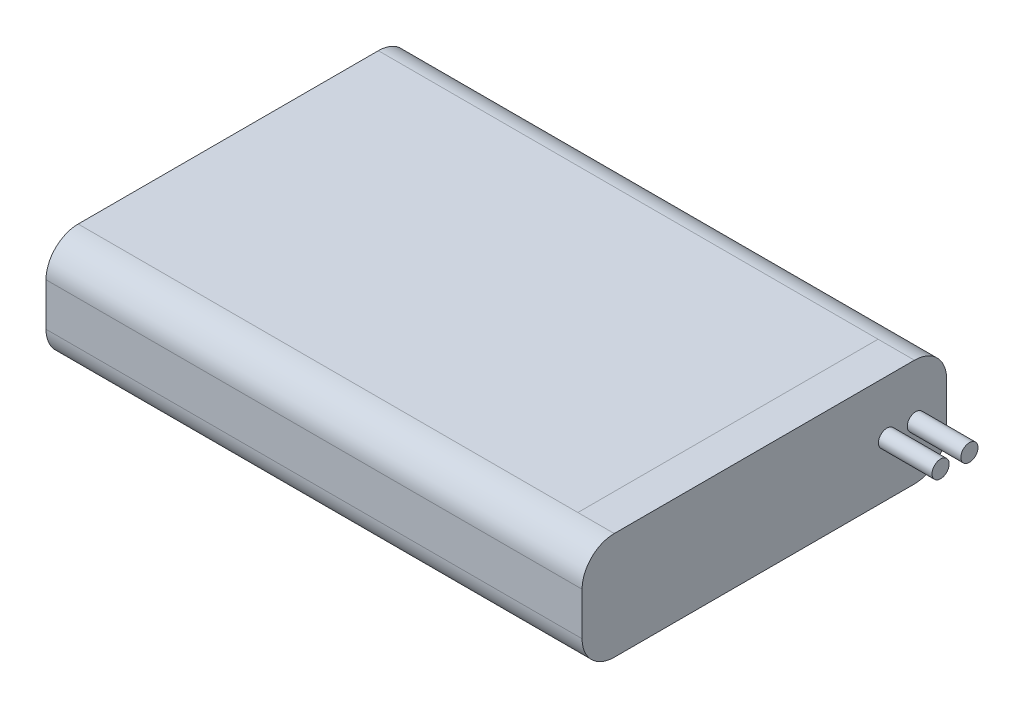
SolidWorks part; units mm, degrees
ref_plane "前视基准面" through (0, 0, 0) normal (0, 0, 1) x (1, 0, 0)
ref_plane "上视基准面" through (0, 0, 0) normal (0, 1, 0) x (1, 0, 0)
ref_plane "右视基准面" through (0, 0, 0) normal (1, 0, 0) x (0, 0, -1)
sketch "草图1" plane through (0, 0, 0) normal (1, 0, 0) x (0, 0, -1)
  line L5 (-13.8102, -5.2821) -> (14.1898, -5.2821)
  line L6 (-16.8102, -2.2821) -> (-16.8102, 1.7179)
  line L7 (-13.8102, 4.7179) -> (14.1898, 4.7179)
  line L8 (17.1898, -2.2821) -> (17.1898, 1.7179)
  arc A0 (-13.8102, -5.2821) -> (-16.8102, -2.2821) centre (-13.8102, -2.2821) cw
  arc A1 (-16.8102, 1.7179) -> (-13.8102, 4.7179) centre (-13.8102, 1.7179) cw
  arc A2 (14.1898, -5.2821) -> (17.1898, -2.2821) centre (14.1898, -2.2821) ccw
  arc A3 (14.1898, 4.7179) -> (17.1898, 1.7179) centre (14.1898, 1.7179) cw
  point P6 (-16.8102, -5.2821)
  point P9 (-16.8102, 4.7179)
  point P12 (17.1898, -5.2821)
  dimension "D3" = 3
  dimension "D4" = 3
  dimension "D5" = 3
  dimension "D6" = 3
  dimension "D1" = 10
  dimension "D2" = 34
extrude "凸台-拉伸2" add sketch "草图1" along normal blind 50
sketch "草图5" plane through (50, 0, 0) normal (1, 0, 0) x (0, 0, -1)
  circle A0 centre (11.6289, -0.2829) radius 0.8
extrude "凸台-拉伸4" add sketch "草图5" along normal blind 5 contours A0
sketch "草图6" plane through (50, 0, 0) normal (1, 0, 0) x (0, 0, -1)
  circle A0 centre (14.3178, -0.3016) radius 0.8
extrude "凸台-拉伸5" add sketch "草图6" along normal blind 5 contours A0
sketch "草图7" plane through (0, 4.7179, 0) normal (0, 1, 0) x (1, 0, 0)
  line L0 (50, -13.8102) -> (0, -13.8102) construction
  line L1 (50, 14.1898) -> (46.6086, 14.1898)
  line L2 (50, 14.1898) -> (50, -13.8102)
  line L3 (50, -13.8102) -> (46.6086, -13.8102)
  line L4 (46.6086, 14.1898) -> (46.6086, -13.8102)
  line L5 (50, 14.1898) -> (0, 14.1898) construction
  point P7 (47.039, 14.1898)
  point P10 (46.6086, -13.8102)
extrude "凸台-拉伸6" add sketch "草图7" along normal blind 0.0001
sketch "草图8" plane through (0, -5.2821, 0) normal (0, -1, 0) x (-1, 0, 0)
  line L1 (-50, -13.8102) -> (-46.6086, -13.8102)
  line L2 (-50, -13.8102) -> (-50, 14.1898)
  line L3 (-50, 14.1898) -> (-46.6086, 14.1898)
  line L4 (-46.6086, -13.8102) -> (-46.6086, 14.1898)
  point P5 (-46.6086, 14.1898)
extrude "凸台-拉伸7" add sketch "草图8" along normal blind 0.0001
